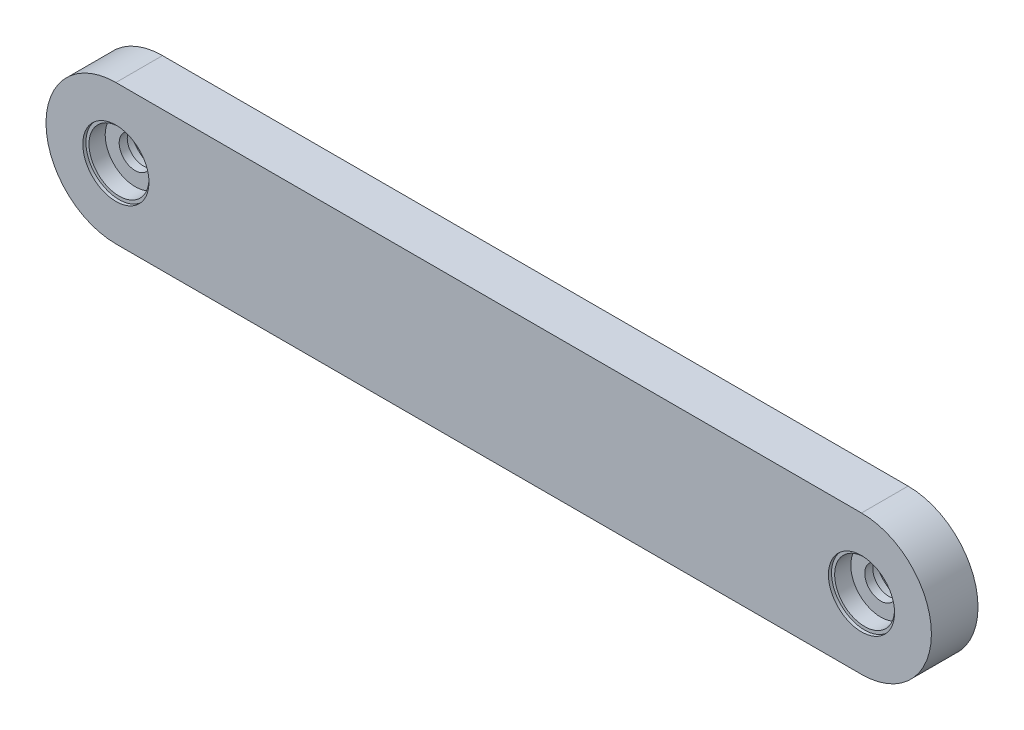
SolidWorks part; units mm, degrees
ref_plane "前视基准面" through (0, 0, 0) normal (0, 0, 1) x (1, 0, 0)
ref_plane "上视基准面" through (0, 0, 0) normal (0, 1, 0) x (1, 0, 0)
ref_plane "右视基准面" through (0, 0, 0) normal (1, 0, 0) x (0, 0, -1)
other "Configuration Table"
ref_plane "基准面2" through (0, 0, 15) normal (0, 0, 1) x (1, 0, 0)
sketch "草图2" plane through (0, 0, 15) normal (0, 0, 1) x (1, 0, 0)
  line L0 (0, -22.5) -> (240, -22.5)
  line L1 (240, 22.5) -> (0, 22.5)
  arc A0 (0, 22.5) -> (0, -22.5) centre (0, 0) ccw
  arc A1 (240, -22.5) -> (240, 22.5) centre (240, 0) ccw
  dimension "D1" = 22.5
  dimension "D2" = 240
extrude "凸台-拉伸1" add sketch "草图2" against normal blind 15
ref_plane "基准面3" through (0, 0, 0) normal (0, -1, 0) x (1, 0, 0)
sketch "草图3" plane through (0, 0, 0) normal (0, -1, 0) x (1, 0, 0)
  line L0 (250.65, 15) -> (240, 15)
  line L1 (240, 15) -> (240, 0)
  line L2 (240, 0) -> (250.65, 0)
  line L3 (250.65, 0) -> (250.65, 1)
  line L4 (250.65, 1) -> (249.65, 1)
  line L5 (249.65, 1) -> (249.65, 6.2)
  line L6 (249.65, 6.2) -> (245.15, 6.2)
  line L7 (245.15, 6.2) -> (245.15, 8.8)
  line L8 (245.15, 8.8) -> (249.65, 8.8)
  line L9 (249.65, 8.8) -> (249.65, 14)
  line L10 (249.65, 14) -> (250.65, 14)
  line L11 (250.65, 14) -> (250.65, 15)
  line L12 (240, 15) -> (240, 0) construction
  dimension "D1" = 5.15
  dimension "D2" = 9.65
  dimension "D3" = 10.65
  dimension "D4" = 1
  dimension "D5" = 6.2
  dimension "D6" = 8.8
  dimension "D7" = 14
  dimension "D8" = 15
revolve "切除-旋转1" cut sketch "草图3" angle 360 about L12
sketch "草图4" plane through (0, 0, 0) normal (0, -1, 0) x (1, 0, 0)
  line L0 (10.65, 15) -> (0, 15)
  line L1 (0, 15) -> (0, 0)
  line L2 (0, 0) -> (10.65, 0)
  line L3 (10.65, 0) -> (10.65, 1)
  line L4 (10.65, 1) -> (9.65, 1)
  line L5 (9.65, 1) -> (9.65, 6.2)
  line L6 (9.65, 6.2) -> (5.15, 6.2)
  line L7 (5.15, 6.2) -> (5.15, 8.8)
  line L8 (5.15, 8.8) -> (9.65, 8.8)
  line L9 (9.65, 8.8) -> (9.65, 14)
  line L10 (9.65, 14) -> (10.65, 14)
  line L11 (10.65, 14) -> (10.65, 15)
  line L12 (0, 15) -> (0, 0) construction
  dimension "D1" = 5.15
  dimension "D2" = 9.65
  dimension "D3" = 10.65
  dimension "D4" = 1
  dimension "D5" = 6.2
  dimension "D6" = 8.8
  dimension "D7" = 14
  dimension "D8" = 15
revolve "切除-旋转2" cut sketch "草图4" angle 360 about L12
